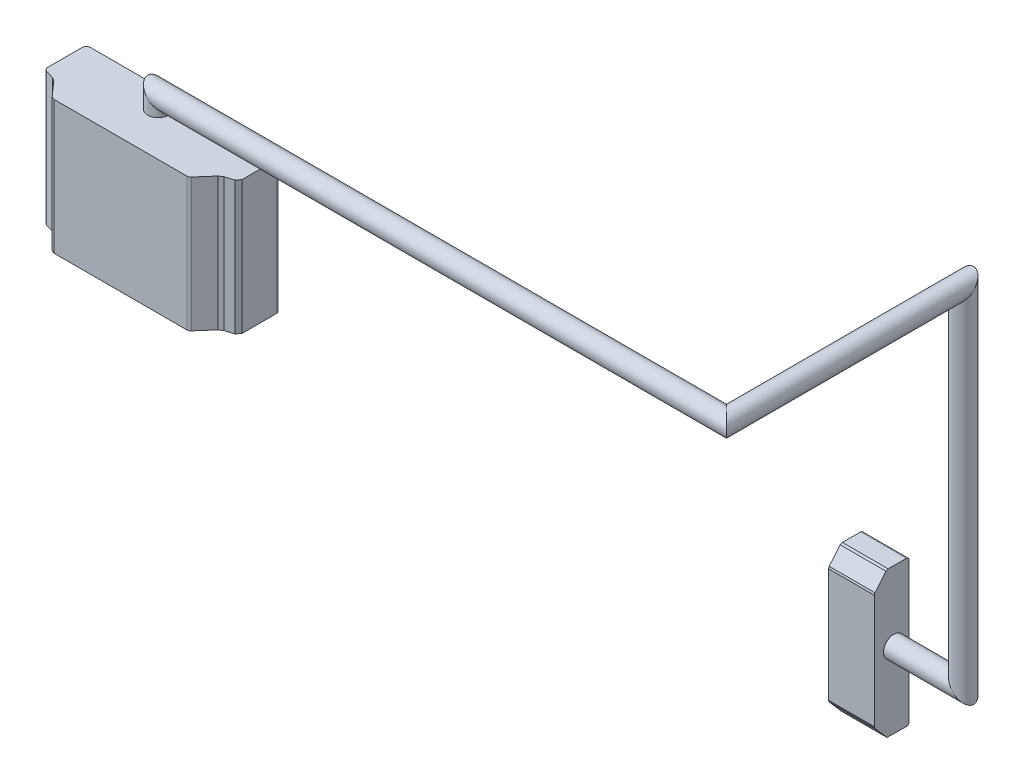
SolidWorks part; units mm, degrees
ref_plane "Plan de face" through (0, 0, 0) normal (0, 0, 1) x (1, 0, 0)
ref_plane "Plan de dessus" through (0, 0, 0) normal (0, 1, 0) x (1, 0, 0)
ref_plane "Plan de droite" through (0, 0, 0) normal (1, 0, 0) x (0, 0, -1)
sketch3d "Esquisse3D1"
  line L0 (0, 0, 0) -> (5, 0, 0)
  line L1 (5, 0, 0) -> (5, 25.07, 0)
  line L2 (5, 25.07, 0) -> (5, 25.07, 17.06)
  line L3 (5, 25.07, 17.06) -> (-35.94, 25.07, 17.06)
  line L4 (-35.94, 25.07, 17.06) -> (-35.94, 24.07, 17.06)
  dimension "D1" = 5
  dimension "D2" = 25.07
  dimension "D3" = 17.06
  dimension "D4" = 40.94
  dimension "D5" = 1
sketch "Esquisse3" plane through (0, 0, 0) normal (1, 0, 0) x (0, 0, -1)
  circle A0 centre (0, 0) radius 0.75
  dimension "D1" = 1.5
sweep "Balayage4" add profiles "Esquisse3" path "Esquisse3D1"
sketch "Esquisse4" plane through (0, 24.07, 0) normal (0, -1, 0) x (1, 0, 0)
  line L0 (-28.5291, 17.1898) -> (-28.7408, 16.903)
  line L1 (-42.2291, 19.9682) -> (-28.8291, 19.9682)
  line L2 (-28.5291, 19.6682) -> (-28.5291, 17.1898)
  line L3 (-28.7408, 16.903) -> (-29.3556, 16.7139)
  line L4 (-29.3556, 16.7139) -> (-29.6067, 16.5515)
  line L5 (-29.6067, 16.5515) -> (-30.5145, 15.52)
  line L6 (-30.7397, 15.4182) -> (-40.3185, 15.4182)
  line L7 (-40.3185, 15.4182) -> (-40.5437, 15.52)
  line L8 (-40.5437, 15.52) -> (-41.4514, 16.5515)
  line L9 (-41.4514, 16.5515) -> (-41.7026, 16.7139)
  line L10 (-41.7026, 16.7139) -> (-42.3173, 16.903)
  line L11 (-42.5291, 17.1898) -> (-42.5291, 19.6682)
  line L12 (5.75, 17.81) -> (-35.94, 17.81) construction
  line L13 (-28.5291, 15.9518) -> (-28.5291, 18.4302)
  line L14 (-42.2291, 15.6518) -> (-28.8291, 15.6518)
  line L15 (-42.5291, 18.4302) -> (-42.5291, 15.9518)
  line L16 (-41.7026, 18.9061) -> (-42.3173, 18.717)
  line L17 (-41.4514, 19.0685) -> (-41.7026, 18.9061)
  line L18 (-40.5437, 20.1) -> (-41.4514, 19.0685)
  line L19 (-40.3185, 20.2018) -> (-40.5437, 20.1)
  line L20 (-30.7397, 20.2018) -> (-40.3185, 20.2018)
  line L21 (-29.6067, 19.0685) -> (-30.5145, 20.1)
  line L22 (-29.3556, 18.9061) -> (-29.6067, 19.0685)
  line L23 (-28.7408, 18.717) -> (-29.3556, 18.9061)
  line L24 (-28.5291, 18.4302) -> (-28.7408, 18.717)
  arc A0 (-28.8291, 19.9682) -> (-28.5291, 19.6682) centre (-28.8291, 19.6682) cw
  arc A1 (-30.5145, 15.52) -> (-30.7397, 15.4182) centre (-30.7397, 15.7182) cw
  arc A2 (-42.3173, 16.903) -> (-42.5291, 17.1898) centre (-42.2291, 17.1898) cw
  arc A3 (-42.5291, 19.6682) -> (-42.2291, 19.9682) centre (-42.2291, 19.6682) cw
  arc A4 (-28.8291, 15.6518) -> (-28.5291, 15.9518) centre (-28.8291, 15.9518) ccw
  arc A5 (-42.5291, 15.9518) -> (-42.2291, 15.6518) centre (-42.2291, 15.9518) ccw
  arc A6 (-42.3173, 18.717) -> (-42.5291, 18.4302) centre (-42.2291, 18.4302) ccw
  arc A7 (-30.5145, 20.1) -> (-30.7397, 20.2018) centre (-30.7397, 19.9018) ccw
extrude "Boss.-Extru.1" add sketch "Esquisse4" along normal blind 9.6 contours L13 L24 L23 L22 L21 A7 L20 L19 L18 L17 L16 A6 L15 A5 L14 A4
sketch "Esquisse5" plane through (0, 0, 0) normal (-1, 0, 0) x (0, 0, 1)
  line L0 (-1.0924, 4.838) -> (-1.0924, -5.262)
  line L1 (-0.8924, -5.462) -> (0.4989, -5.4433)
  line L2 (0.4989, -5.4433) -> (1.361, -4.4428)
  line L3 (1.361, -4.4428) -> (1.4076, -4.3144)
  line L4 (1.4076, -4.3144) -> (1.4076, 3.8903)
  line L5 (1.4076, 3.8903) -> (1.361, 4.0187)
  line L6 (1.361, 4.0187) -> (0.5676, 4.9663)
  line L7 (0.5676, 4.9663) -> (0.4142, 5.038)
  line L8 (0.4142, 5.038) -> (-0.8924, 5.038)
  arc A0 (-1.0924, -5.262) -> (-0.8924, -5.462) centre (-0.8924, -5.262) ccw
  arc A1 (-0.8924, 5.038) -> (-1.0924, 4.838) centre (-0.8924, 4.838) ccw
extrude "Boss.-Extru.2" add sketch "Esquisse5" along normal blind 3.3 contours L0 A0 L1 L2 L3 L4 L5 L6 L7 L8 A1
